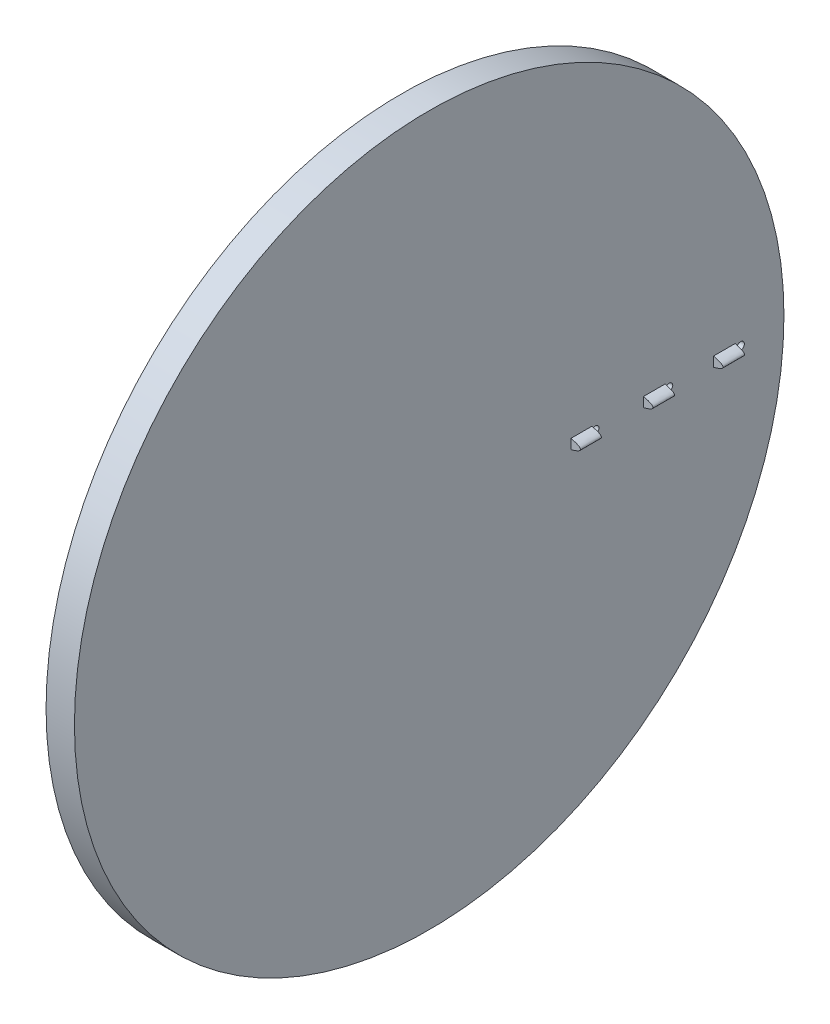
SolidWorks part; units mm, degrees
ref_plane "Alzado" through (0, 0, 0) normal (0, 0, 1) x (1, 0, 0)
ref_plane "Planta" through (0, 0, 0) normal (0, 1, 0) x (1, 0, 0)
ref_plane "Vista lateral" through (0, 0, 0) normal (1, 0, 0) x (0, 0, -1)
sketch "Croquis1" plane through (0, 0, 0) normal (1, 0, 0) x (0, 0, -1)
  circle A0 centre (0, 0) radius 37.5
  dimension "D1" = 75
extrude "Saliente-Extruir1" add sketch "Croquis1" along normal blind 3
sketch "Croquis3" plane through (3, 0, 0) normal (1, 0, 0) x (0, 0, -1)
  line L0 (0, 0) -> (37.5, 0) construction
  line L1 (14.9919, -1.0312) -> (17.2081, 0) construction
  line L2 (14.9919, 0) -> (17.2081, 0)
  line L3 (14.9919, 0) -> (14.9919, -1.0312)
  line L4 (14.9919, -1.0312) -> (17.2081, -1.0312)
  line L5 (17.2081, 0) -> (17.2081, -1.0312)
  line L6 (17.2081, -1.0312) -> (16.1, -0.5156) construction
  line L7 (22.6612, -1.0312) -> (24.9388, 0) construction
  line L12 (22.6612, 0) -> (24.9388, 0)
  line L13 (22.6612, 0) -> (22.6612, -1.0312)
  line L18 (22.6612, -1.0312) -> (24.9388, -1.0312)
  line L19 (24.9388, 0) -> (24.9388, -1.0312)
  line L20 (30.0612, 0) -> (32.3388, 0)
  line L21 (30.0612, 0) -> (30.0612, -1.0312)
  line L22 (30.0612, -1.0312) -> (32.3388, -1.0312)
  line L23 (32.3388, 0) -> (32.3388, -1.0312)
  line L24 (24.9388, -1.0312) -> (23.8, -0.5156) construction
  line L25 (30.0612, -1.0312) -> (32.3388, 0) construction
  line L26 (31.2, -0.5156) -> (32.3388, -1.0312) construction
  circle A0 centre (0, 0) radius 37.5 construction
  point P21 (0, 0)
  point P22 (0, 0)
  dimension "D1" = 16.1
  dimension "D2" = 23.8
  dimension "D3" = 31.2
extrude "Saliente-Extruir2" add sketch "Croquis3" along normal blind 1
sketch "Croquis4" plane through (0, 0, -32.3388) normal (0, 0, -1) x (-1, 0, 0)
  line L0 (-3, 37.5) -> (-3, -37.5) construction
  line L1 (-4, -1.0312) -> (-4, 0) construction
  line L2 (-3, 0) -> (-3, -1.0312)
  line L3 (-4, -1.0312) -> (-3, -1.0312)
  line L4 (-4, -1.0312) -> (-4, 0)
  line L5 (-4, 0) -> (-4.0068, 0.0018)
  line L6 (-3, 0) -> (-4, 0)
  spline S0 degree 2 poles (-3, 0) (-5, -0.5156) (-3, -1.0312) knots 0 0 0 1 1 1
  line M3 (-3, 0) -> (-4, 0)
  line M4 (-4, 0) -> (-4, -1.0312)
  line M5 (-4, -1.0312) -> (-3, -1.0312)
extrude "Cortar-Extruir1" cut sketch "Croquis4" against normal blind 20 contours S0 M3 M4 | S0 L4 M5
sketch "Croquis5" plane through (3, 0, 0) normal (1, 0, 0) x (0, 0, -1)
  line L0 (17.2081, -0.5156) -> (37.4965, -0.5156) construction
  line L1 (17.2081, -1.0312) -> (17.2081, 0) construction
  circle A0 centre (0, 0) radius 37.5 construction
  circle A1 centre (17.5862, -0.5156) radius 0.3597
  circle A2 centre (25.3808, -0.5156) radius 0.3652
  circle A3 centre (32.9156, -0.5156) radius 0.4003
extrude "Cortar-Extruir2" cut sketch "Croquis5" against normal blind 20
